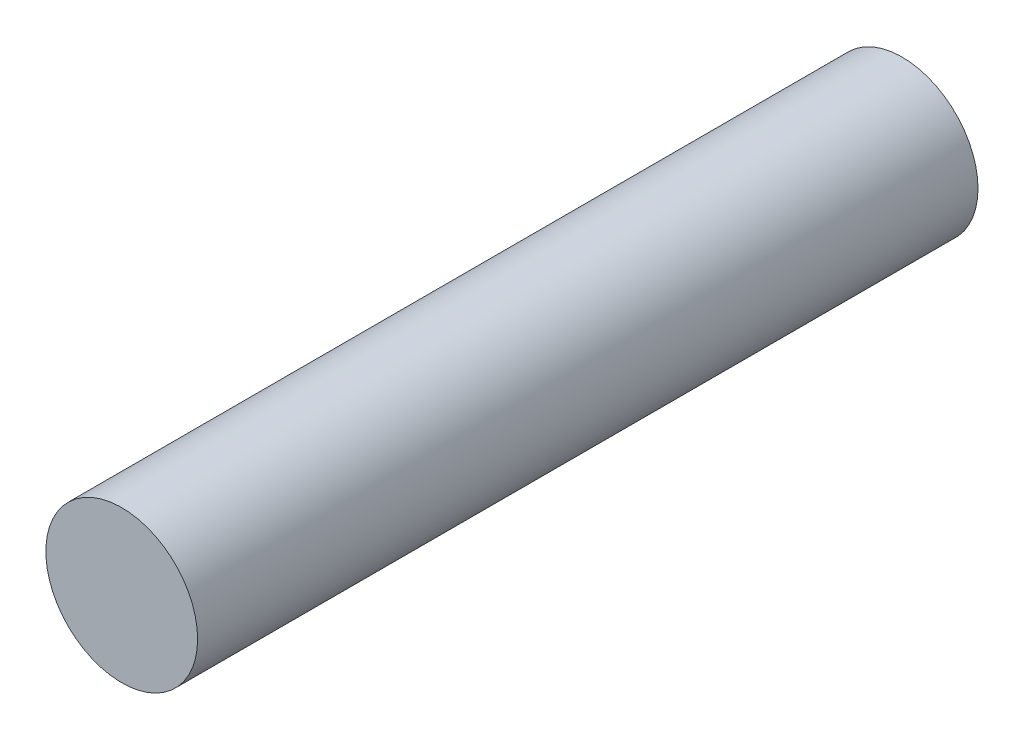
SolidWorks part; units mm, degrees
ref_plane "Front Plane" through (0, 0, 0) normal (0, 0, 1) x (1, 0, 0)
ref_plane "Top Plane" through (0, 0, 0) normal (0, 1, 0) x (1, 0, 0)
ref_plane "Right Plane" through (0, 0, 0) normal (1, 0, 0) x (0, 0, -1)
sketch "Sketch1" plane through (0, 0, 0) normal (0, 0, 1) x (1, 0, 0)
  circle A0 centre (0, 0) radius 3.5
extrude "Extrude1" add sketch "Sketch1" along normal mid plane 36
